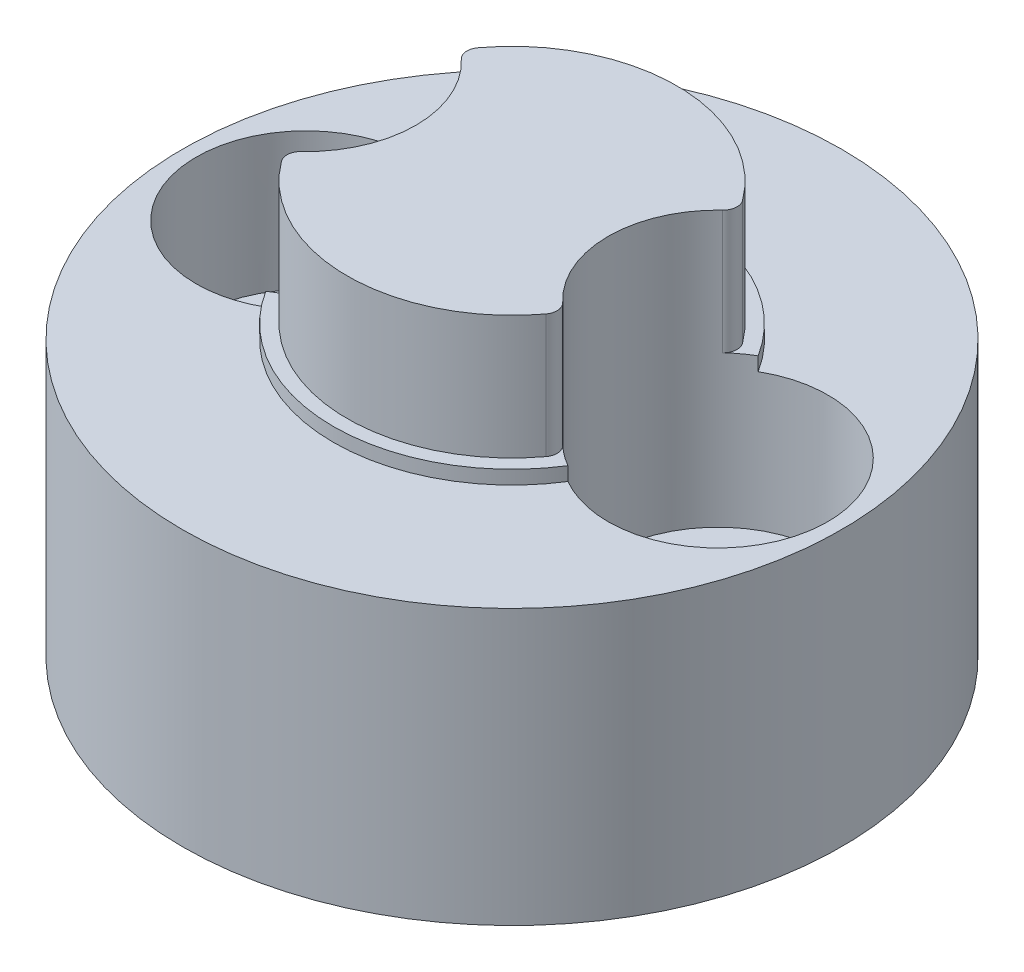
SolidWorks part; units mm, degrees
material "5052-H34"
ref_plane "正面" through (0, 0, 0) normal (0, 0, 1) x (1, 0, 0)
ref_plane "平面" through (0, 0, 0) normal (0, 1, 0) x (1, 0, 0)
ref_plane "右側面" through (0, 0, 0) normal (1, 0, 0) x (0, 0, -1)
sketch "ｽｹｯﾁ1" plane through (0, 0, 0) normal (0, 1, 0) x (1, 0, 0)
  line L0 (0, 0) -> (0, 12) construction
  circle A0 centre (0, 0) radius 12
  circle A1 centre (-7.5, 0) radius 2.15
  circle A2 centre (7.5, 0) radius 2.15
  dimension "D1" = 24
  dimension "D2" = 4.3
  dimension "D3" = 15
extrude "ﾎﾞｽ - 押し出し1" add sketch "ｽｹｯﾁ1" along normal blind 15
sketch "ｽｹｯﾁ2" plane through (0, 15, 0) normal (0, 1, 0) x (1, 0, 0)
  circle A1 centre (0, 0) radius 12 construction
  circle A2 centre (0, 0) radius 12
  arc A3 (5.8418, 1.3686) -> (-5.8418, 1.3686) centre (0, 0) ccw
  circle A4 centre (7.5, 0) radius 2.15 construction
  circle A5 centre (-7.5, 0) radius 2.15 construction
  arc A6 (5.8418, 1.3686) -> (5.8418, -1.3686) centre (7.5, 0) ccw
  arc A7 (-5.8418, -1.3686) -> (-5.8418, 1.3686) centre (-7.5, 0) ccw
  arc A8 (-5.8418, -1.3686) -> (5.8418, -1.3686) centre (0, 0) ccw
  dimension "D1" = 12
extrude "ｶｯﾄ - 押し出し1" cut sketch "ｽｹｯﾁ2" against normal blind 5
sketch "ｽｹｯﾁ3" plane through (0, 10, 0) normal (0, 1, 0) x (1, 0, 0)
  arc A1 (-6.2585, -1.7553) -> (6.2585, -1.7553) centre (0, 0) ccw
  arc A2 (5.8418, 1.3686) -> (-5.8418, 1.3686) centre (0, 0) ccw construction
  arc A4 (5.8418, -1.3686) -> (5.8418, 1.3686) centre (7.5, 0) ccw construction
  arc A5 (5.8418, 1.3686) -> (5.8418, -1.3686) centre (7.5, 0) ccw construction
  arc A6 (-5.8418, 1.3686) -> (-5.8418, -1.3686) centre (-7.5, 0) ccw construction
  arc A7 (-5.8418, -1.3686) -> (-5.8418, 1.3686) centre (-7.5, 0) ccw construction
  arc A8 (5.8418, -1.3686) -> (6.2585, -1.7553) centre (7.5, 0) ccw
  arc A9 (5.8418, 1.3686) -> (5.8418, -1.3686) centre (7.5, 0) ccw
  arc A10 (-5.8418, 1.3686) -> (-6.2585, 1.7553) centre (-7.5, 0) ccw
  arc A11 (-5.8418, -1.3686) -> (-5.8418, 1.3686) centre (-7.5, 0) ccw
  arc A12 (-6.2585, -1.7553) -> (-5.8418, -1.3686) centre (-7.5, 0) ccw
  arc A13 (6.2585, 1.7553) -> (-6.2585, 1.7553) centre (0, 0) ccw
  arc A14 (6.2585, 1.7553) -> (5.8418, 1.3686) centre (7.5, 0) ccw
  dimension "D1" = 0.5
extrude "ﾎﾞｽ - 押し出し2" add sketch "ｽｹｯﾁ3" along normal blind 0.5
sketch "ｽｹｯﾁ4" plane through (0, 15, 0) normal (0, 1, 0) x (1, 0, 0)
  circle A0 centre (-7.5, 0) radius 4
  circle A1 centre (7.5, 0) radius 4
  dimension "D1" = 8
extrude "ｶｯﾄ - 押し出し2" cut sketch "ｽｹｯﾁ4" against normal blind 10
fillet "ﾌｨﾚｯﾄ1" radius 0.5 4 edges at (-5.0833, 12.75, -3.1874) (-5.0833, 12.75, 3.1874) (5.0833, 12.75, -3.1874) (5.0833, 12.75, 3.1874)
